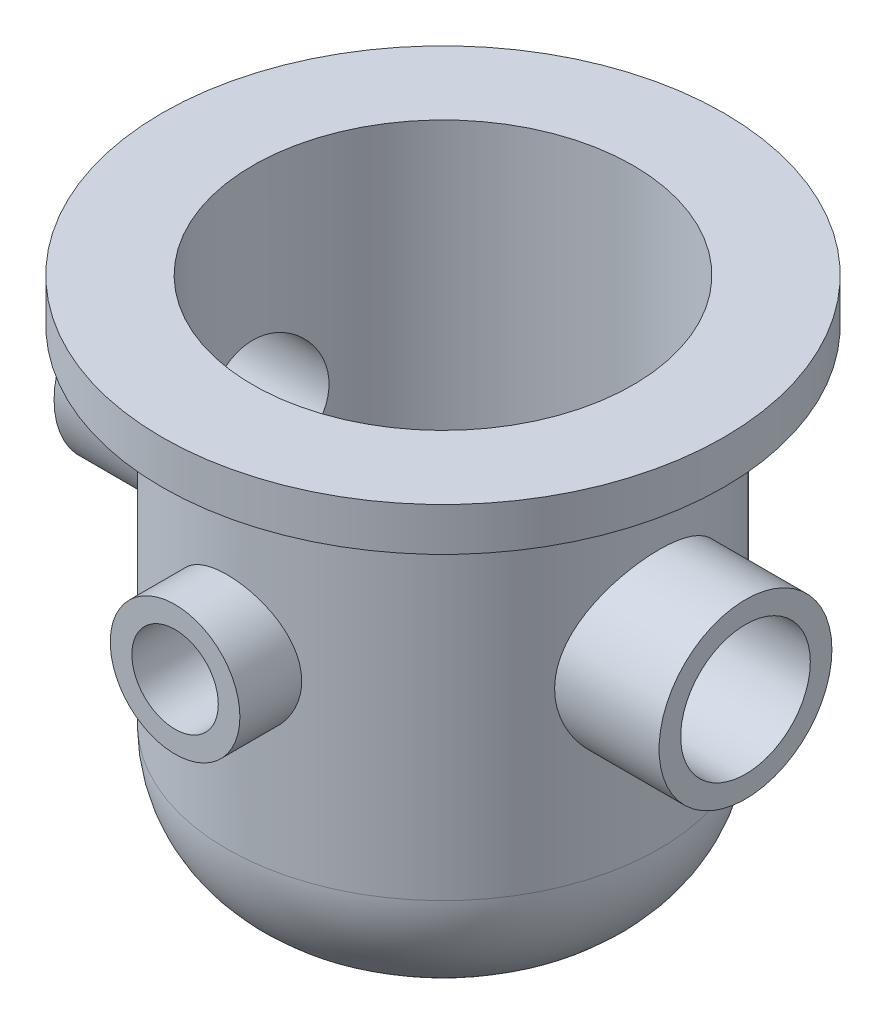
SolidWorks part; units mm, degrees
material "Plain Carbon Steel"
ref_plane "Front Plane" through (0, 0, 0) normal (0, 0, 1) x (1, 0, 0)
ref_plane "Top Plane" through (0, 0, 0) normal (0, 1, 0) x (1, 0, 0)
ref_plane "Right Plane" through (0, 0, 0) normal (1, 0, 0) x (0, 0, -1)
sketch "Sketch1" plane through (0, 0, 0) normal (0, 0, 1) x (1, 0, 0)
  line L0 (0, 0) -> (0, 121.3676) construction
  line L1 (-31.75, 69.85) -> (-31.75, 19.05)
  line L2 (-12.7, 0) -> (0, 0)
  line L3 (-27.94, 76.2) -> (-27.94, 19.05)
  line L4 (-12.7, 3.81) -> (0, 3.81)
  line L5 (-27.94, 76.2) -> (-41.275, 76.2)
  line L6 (-41.275, 76.2) -> (-41.275, 69.85)
  line L7 (-41.275, 69.85) -> (-31.75, 69.85)
  line L8 (-31.75, 76.2) -> (-31.75, 19.05) construction
  line L9 (0, 3.81) -> (0, 0)
  arc A0 (-31.75, 19.05) -> (-12.7, 0) centre (-12.7, 19.05) ccw
  arc A1 (-27.94, 19.05) -> (-12.7, 3.81) centre (-12.7, 19.05) ccw
  dimension "D3" = 19.05
  dimension "D1" = 82.55
  dimension "D2" = 63.5
  dimension "D5" = 76.2
  dimension "D6" = 6.35
  dimension "D4" = 3.81
revolve "Revolve1" add sketch "Sketch1" angle 360 about L0
ref_plane "Plane1" through (44.45, 0, 0) normal (1, 0, 0) x (0, 0, -1)
sketch "Sketch2" plane through (44.45, 0, 0) normal (1, 0, 0) x (0, 0, -1)
  line L0 (27.94, 76.2) -> (-27.94, 76.2) construction
  line L1 (0, 0) -> (0, 76.2) construction
  line L2 (41.275, 76.2) -> (-41.275, 76.2) construction
  circle A0 centre (0, 44.45) radius 12.7
  dimension "D1" = 25.4
  dimension "D2" = 31.75
extrude "Boss-Extrude1" add sketch "Sketch2" against normal up to next
sketch "Sketch3" plane through (44.45, 0, 0) normal (1, 0, 0) x (0, 0, -1)
  circle A0 centre (0, 44.45) radius 9.525
  dimension "D1" = 19.05
extrude "Cut-Extrude1" cut sketch "Sketch3" against normal up to next
mirror "Mirror3" about plane through (0, 0, 0) normal (1, 0, 0) of "Cut-Extrude1", "Boss-Extrude1"
ref_plane "Plane2" through (0, 0, 39.37) normal (0, 0, 1) x (1, 0, 0)
sketch "Sketch4" plane through (0, 0, 39.37) normal (0, 0, 1) x (1, 0, 0)
  line L0 (0, 0) -> (0, 76.2) construction
  line L1 (27.94, 76.2) -> (-27.94, 76.2) construction
  line L2 (-44.45, 44.45) -> (44.45, 44.45) construction
  line L3 (-44.45, 57.15) -> (-44.45, 31.75) construction
  line L4 (44.45, 31.75) -> (44.45, 57.15) construction
  circle A0 centre (0, 44.45) radius 9.525
  dimension "D1" = 19.05
extrude "Boss-Extrude2" add sketch "Sketch4" against normal up to next
sketch "Sketch5" plane through (0, 0, 39.37) normal (0, 0, 1) x (1, 0, 0)
  circle A0 centre (0, 44.45) radius 6.35
  dimension "D1" = 12.7
extrude "Cut-Extrude2" cut sketch "Sketch5" against normal up to next
sketch "Sketch6" plane through (0, 0, 0) normal (0, -1, 0) x (1, 0, 0)
  circle A0 centre (0, 0) radius 9.525
  dimension "D1" = 19.05
extrude "Boss-Extrude3" add sketch "Sketch6" along normal blind 6.35
sketch "Sketch7" plane through (0, -6.35, 0) normal (0, -1, 0) x (1, 0, 0)
  circle A0 centre (0, 0) radius 6.35
  dimension "D1" = 12.7
extrude "Cut-Extrude3" cut sketch "Sketch7" against normal up to next
